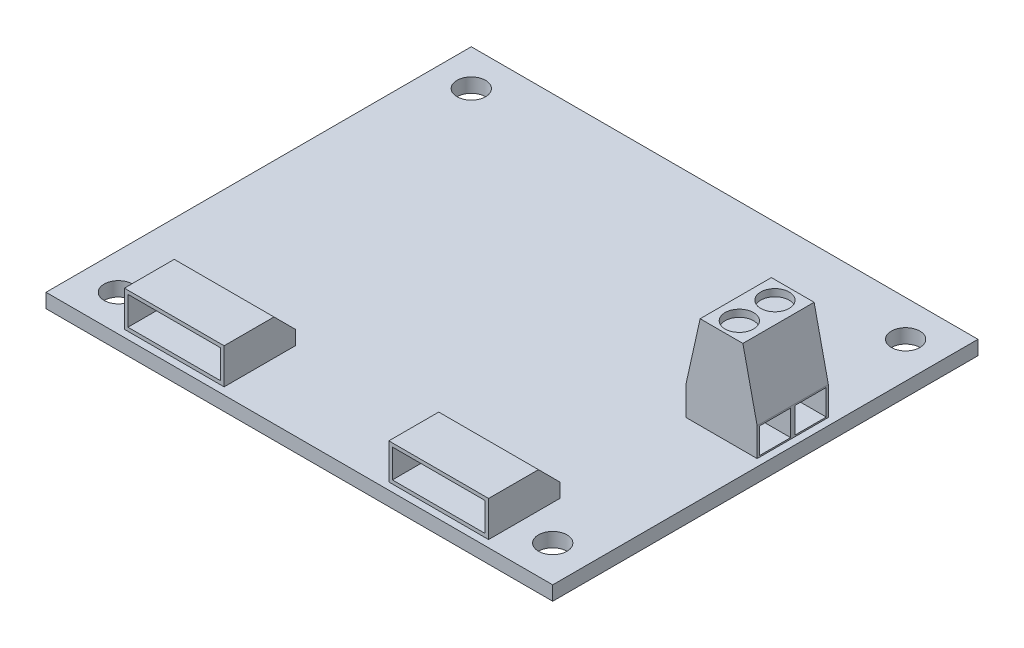
SolidWorks part; units mm, degrees
material "Silicon"
ref_plane "Front Plane" through (0, 0, 0) normal (0, 0, 1) x (1, 0, 0)
ref_plane "Top Plane" through (0, 0, 0) normal (0, 1, 0) x (1, 0, 0)
ref_plane "Right Plane" through (0, 0, 0) normal (1, 0, 0) x (0, 0, -1)
sketch "Sketch1" plane through (0, 0, 0) normal (0, 1, 0) x (1, 0, 0)
  line L0 (0, -29.845) -> (0, 29.845) construction
  line L1 (-35.56, 29.845) -> (35.56, 29.845)
  line L2 (-35.56, 29.845) -> (-35.56, -29.845)
  line L3 (-35.56, -29.845) -> (35.56, -29.845)
  line L4 (35.56, 29.845) -> (35.56, -29.845)
  dimension "D1" = 71.12
  dimension "D2" = 59.69
extrude "Boss-Extrude1" add sketch "Sketch1" along normal blind 2
sketch "Sketch2" plane through (0, 2, 0) normal (0, 1, 0) x (1, 0, 0)
  line L1 (-30.48, 24.765) -> (30.48, 24.765) construction
  line L2 (0, 0) -> (-35.56, 0) construction
  line L3 (30.48, -24.765) -> (0, -24.765) construction
  line L4 (30.48, 24.765) -> (30.48, -24.765) construction
  line L6 (0, -29.845) -> (0, 0) construction
  line L7 (-35.56, -29.845) -> (35.56, -29.845) construction
  line L8 (0, -24.765) -> (-30.48, -24.765) construction
  line L9 (-35.56, 29.845) -> (-35.56, -29.845) construction
  line L10 (-30.48, 24.765) -> (-30.48, 0) construction
  line L11 (-30.48, 0) -> (-30.48, -24.765) construction
  circle A0 centre (-30.48, 24.765) radius 2
  circle A1 centre (30.48, 24.765) radius 2
  circle A2 centre (30.48, -24.765) radius 2
  circle A3 centre (-30.48, -24.765) radius 2
  dimension "D5" = 4
  dimension "D3" = 60.96
  dimension "D4" = 49.53
extrude "Cut-Extrude1" cut sketch "Sketch2" against normal blind 2
sketch "Sketch3" plane through (0, 2, 0) normal (0, 1, 0) x (1, 0, 0)
  line L0 (0, -29.845) -> (0, 29.845) construction
  line L1 (-11.56, -28.845) -> (-25.56, -28.845)
  line L2 (-11.56, -28.845) -> (-11.56, -18.845)
  line L3 (-11.56, -18.845) -> (-25.56, -18.845)
  line L4 (-25.56, -28.845) -> (-25.56, -18.845)
  line L5 (-35.56, -29.845) -> (35.56, -29.845) construction
  line L6 (35.56, 29.845) -> (-35.56, 29.845) construction
  line L7 (11.56, -28.845) -> (25.56, -28.845)
  line L8 (25.56, -28.845) -> (25.56, -18.845)
  line L9 (11.56, -28.845) -> (11.56, -18.845)
  line L10 (11.56, -18.845) -> (25.56, -18.845)
  line L11 (-35.56, 29.845) -> (-35.56, -29.845) construction
  dimension "D1" = 14
  dimension "D2" = 10
  dimension "D3" = 10
  dimension "D4" = 1
extrude "Boss-Extrude2" add sketch "Sketch3" along normal blind 5
sketch "Sketch4" plane through (0, 2, 0) normal (0, 1, 0) x (1, 0, 0)
  line L0 (35.56, 29.845) -> (-35.56, 29.845) construction
  line L1 (24.56, 9.845) -> (34.56, 9.845)
  line L2 (24.56, 9.845) -> (24.56, -0.155)
  line L3 (24.56, -0.155) -> (34.56, -0.155)
  line L4 (34.56, 9.845) -> (34.56, -0.155)
  line L5 (35.56, -29.845) -> (35.56, 29.845) construction
  dimension "D1" = 20
  dimension "D2" = 1
  dimension "D3" = 10
extrude "Boss-Extrude3" add sketch "Sketch4" along normal blind 13
sketch "Sketch7" plane through (0, 0, 0.155) normal (0, 0, 1) x (1, 0, 0)
  line L0 (26.56, 15) -> (24.56, 6)
  line L1 (24.56, 15) -> (34.56, 15) construction
  line L3 (24.56, 15) -> (24.56, 2) construction
  line L4 (24.56, 6) -> (34.56, 6) construction
  line L5 (34.56, 15) -> (34.56, 2) construction
  line L6 (34.56, 6) -> (32.56, 15)
  line L7 (32.56, 15) -> (26.56, 15) construction
  line L8 (24.56, 2) -> (34.56, 2) construction
  line L9 (34.56, 6) -> (34.56, 15)
  line L10 (34.56, 15) -> (32.56, 15)
  line L11 (26.56, 15) -> (24.56, 15)
  line L12 (24.56, 15) -> (24.56, 6)
  dimension "D1" = 6
  dimension "D2" = 4
extrude "Cut-Extrude2" cut sketch "Sketch7" against normal through all
sketch "Sketch8" plane through (0, 0, 28.845) normal (0, 0, 1) x (1, 0, 0)
  line L0 (0, 0) -> (0, 22.4175) construction
  line L1 (-35.56, 0) -> (35.56, 0) construction
  line L2 (-25.56, 7) -> (-11.56, 7) construction
  line L3 (-25.06, 6.5) -> (-12.06, 6.5)
  line L4 (-25.06, 6.5) -> (-25.06, 2.5)
  line L5 (-25.06, 2.5) -> (-12.06, 2.5)
  line L6 (-12.06, 6.5) -> (-12.06, 2.5)
  line L7 (-25.56, 7) -> (-25.56, 2) construction
  line L8 (25.06, 2.5) -> (12.06, 2.5)
  line L9 (12.06, 6.5) -> (12.06, 2.5)
  line L10 (25.06, 6.5) -> (12.06, 6.5)
  line L11 (25.06, 6.5) -> (25.06, 2.5)
  point P8 (-18.56, 6.5)
  point P11 (-18.56, 7)
  point P14 (-25.06, 4.5)
  point P15 (-25.56, 4.5)
  dimension "D1" = 0.5
  dimension "D2" = 0.5
extrude "Cut-Extrude3" cut sketch "Sketch8" against normal blind 7
chamfer "Chamfer1" distance 3 angle 45 2 edges at (-18.56, 7, 18.845) (18.56, 7, 18.845)
sketch "Sketch9" plane through (34.56, 0, 0) normal (1, 0, 0) x (0, 0, -1)
  line L0 (4.845, 6) -> (4.845, 2) construction
  line L1 (9.845, 6) -> (-0.155, 6) construction
  line L2 (-0.155, 2) -> (9.845, 2) construction
  line L3 (4.845, 4) -> (-0.155, 4) construction
  line L4 (-0.155, 6) -> (-0.155, 2) construction
  line L5 (9.545, 2.2) -> (5.145, 2.2)
  line L6 (0.145, 5.8) -> (4.545, 5.8)
  line L7 (0.145, 5.8) -> (0.145, 2.2)
  line L8 (0.145, 2.2) -> (4.545, 2.2)
  line L9 (4.545, 5.8) -> (4.545, 2.2)
  line L10 (0.145, 5.8) -> (4.545, 2.2) construction
  line L11 (0.145, 2.2) -> (4.545, 5.8) construction
  line L12 (5.145, 5.8) -> (5.145, 2.2)
  line L13 (9.545, 5.8) -> (5.145, 5.8)
  line L14 (9.545, 5.8) -> (9.545, 2.2)
  point P10 (2.345, 4)
  dimension "D1" = 0.2
  dimension "D2" = 0.3
extrude "Cut-Extrude4" cut sketch "Sketch9" against normal blind 8
sketch "Sketch10" plane through (0, 15, 0) normal (0, 1, 0) x (1, 0, 0)
  line L0 (26.56, 4.845) -> (32.56, 4.845) construction
  line L1 (26.56, -0.155) -> (26.56, 9.845) construction
  line L2 (32.56, 9.845) -> (32.56, -0.155) construction
  line L3 (29.56, 4.845) -> (29.56, 9.845) construction
  line L4 (32.56, 9.845) -> (26.56, 9.845) construction
  circle A0 centre (29.56, 7.345) radius 2
  circle A1 centre (29.56, 2.345) radius 2
  dimension "D1" = 4
extrude "Cut-Extrude5" cut sketch "Sketch10" against normal blind 1
